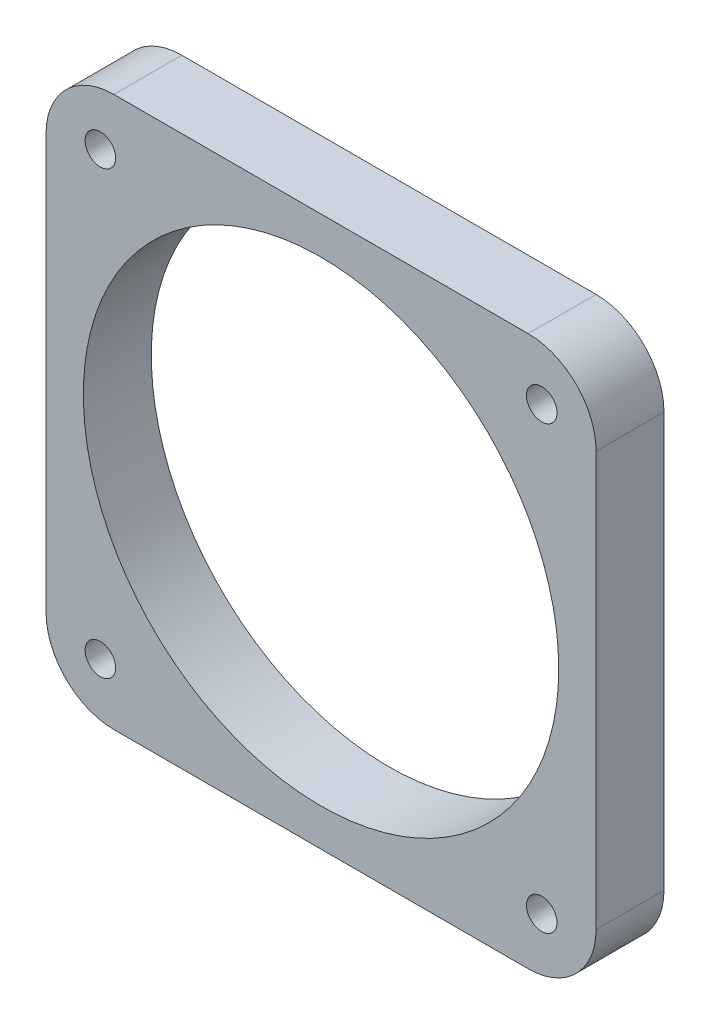
SolidWorks part; units mm, degrees
ref_plane "Ön Düzlem" through (0, 0, 0) normal (0, 0, 1) x (1, 0, 0)
ref_plane "Üst Düzlem" through (0, 0, 0) normal (0, 1, 0) x (1, 0, 0)
ref_plane "Sağ Düzlem" through (0, 0, 0) normal (1, 0, 0) x (0, 0, -1)
sketch "Sketch1" plane through (0, 0, 0) normal (0, 0, 1) x (1, 0, 0)
  line L1 (-61, -81) -> (61, -81)
  line L2 (-81, -61) -> (-81, 61)
  line L3 (-61, 81) -> (61, 81)
  line L4 (81, -61) -> (81, 61)
  line L5 (-81, -81) -> (81, 81) construction
  line L6 (-81, 81) -> (81, -81) construction
  circle A0 centre (-65, 65) radius 4.5
  circle A1 centre (65, 65) radius 4.5
  circle A2 centre (65, -65) radius 4.5
  circle A3 centre (-65, -65) radius 4.5
  circle A4 centre (0, 0) radius 70
  arc A5 (-61, -81) -> (-81, -61) centre (-61, -61) cw
  arc A6 (61, -81) -> (81, -61) centre (61, -61) ccw
  arc A7 (61, 81) -> (81, 61) centre (61, 61) cw
  arc A8 (-81, 61) -> (-61, 81) centre (-61, 61) cw
  point P0 (0, 0)
  dimension "D3" = 9
  dimension "D4" = 140
  dimension "D5" = 20
  dimension "D1" = 162
  dimension "D2" = 130
extrude "Boss-Extrude1" add sketch "Sketch1" along normal blind 20
